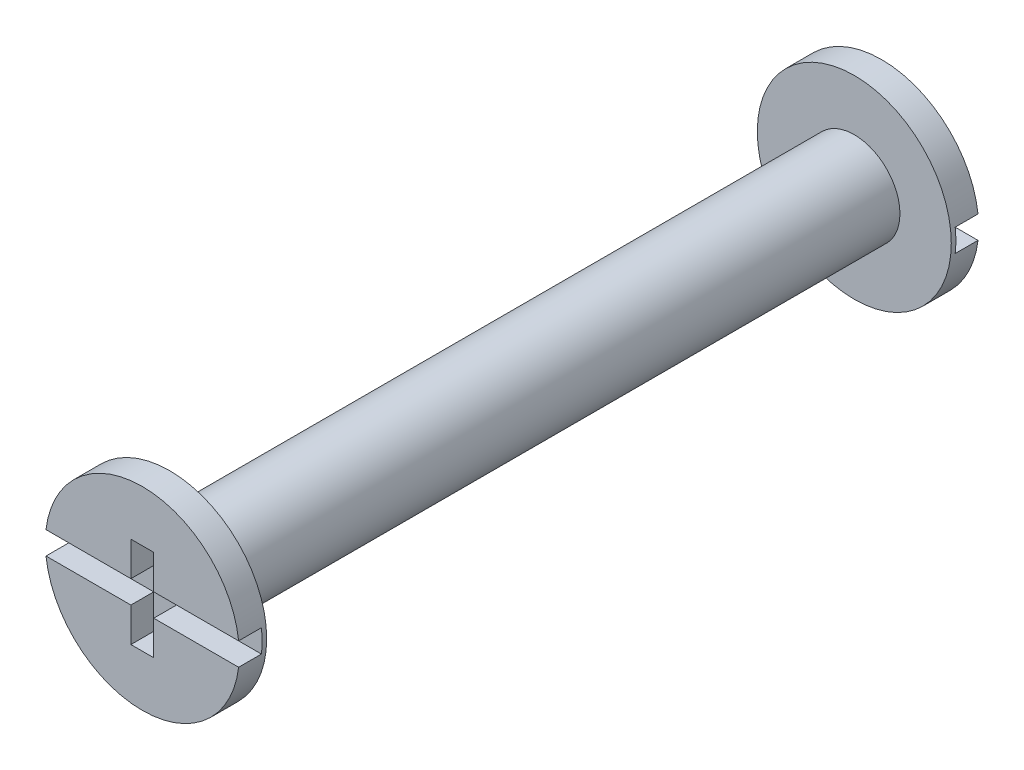
SolidWorks part; units mm, degrees
material "镀铬不锈钢"
ref_plane "前视基准面" through (0, 0, 0) normal (0, 0, 1) x (1, 0, 0)
ref_plane "上视基准面" through (0, 0, 0) normal (0, 1, 0) x (1, 0, 0)
ref_plane "右视基准面" through (0, 0, 0) normal (1, 0, 0) x (0, 0, -1)
sketch "草图1" plane through (0, 0, 0) normal (0, 0, 1) x (1, 0, 0)
  circle A0 centre (0, 0) radius 4.25
  dimension "D1" = 8.5
extrude "凸台-拉伸1" add sketch "草图1" along normal blind 1.2
sketch "草图2" plane through (0, 0, 1.2) normal (0, 0, 1) x (1, 0, 0)
  circle A0 centre (0, 0) radius 2
  dimension "D1" = 4
extrude "凸台-拉伸2" add sketch "草图2" along normal blind 30
sketch "草图3" plane through (0, 0, 31.2) normal (0, 0, 1) x (1, 0, 0)
  circle A0 centre (0, 0) radius 4.25
  dimension "D1" = 8.5
extrude "凸台-拉伸3" add sketch "草图3" along normal blind 1.2
sketch "草图4" plane through (0, 0, 32.4) normal (0, 0, 1) x (1, 0, 0)
  line L1 (0, -0.8601) -> (0, -2) construction
  line L2 (-0.5, 2) -> (-0.5, 0.5)
  line L3 (0.5, 2) -> (0.5, 0.5)
  line L4 (-4.7236, -0.5) -> (-0.5, -0.5)
  line L5 (-4.7236, 0.5) -> (-0.5, 0.5)
  line L8 (-0.5, 4.75) -> (-0.5, -4.75) construction
  line L9 (0.5, 4.75) -> (0.5, -4.75) construction
  line L10 (0, 4.75) -> (0, -4.75) construction
  line L13 (-0.5, 2) -> (0.5, 2)
  line L14 (-0.5, -2) -> (0.5, -2)
  line L17 (0.5, -0.5) -> (4.7236, -0.5)
  line L21 (0.5, 0.5) -> (4.7236, 0.5)
  line L23 (-0.5, -0.5) -> (-0.5, -2)
  line L24 (0.5, -0.5) -> (0.5, -2)
  arc A2 (-4.7236, 0.5) -> (-4.7236, -0.5) centre (0, 0) ccw
  arc A3 (4.7236, -0.5) -> (4.7236, 0.5) centre (0, 0) ccw
  dimension "D1" = 0.5
  dimension "D2" = 0.5
extrude "切除-拉伸1" cut sketch "草图4" against normal blind 1
sketch "草图5" plane through (0, 0, 0) normal (0, 0, -1) x (-1, 0, 0)
  line L0 (-4.25, 0) -> (4.25, 0) construction
  line L1 (-4.7236, -0.5) -> (4.7236, -0.5)
  line L2 (-4.7236, 0.5) -> (4.7236, 0.5)
  line L3 (-4.25, -0.5) -> (4.25, -0.5) construction
  line L4 (-4.25, 0.5) -> (4.25, 0.5) construction
  circle A0 centre (0, 0) radius 4.25 construction
  arc A1 (-4.7236, 0.5) -> (-4.7236, -0.5) centre (0, 0) ccw
  arc A2 (4.7236, -0.5) -> (4.7236, 0.5) centre (0, 0) ccw
  dimension "D1" = 0.5
  dimension "D2" = 0.5
extrude "切除-拉伸2" cut sketch "草图5" against normal blind 1
